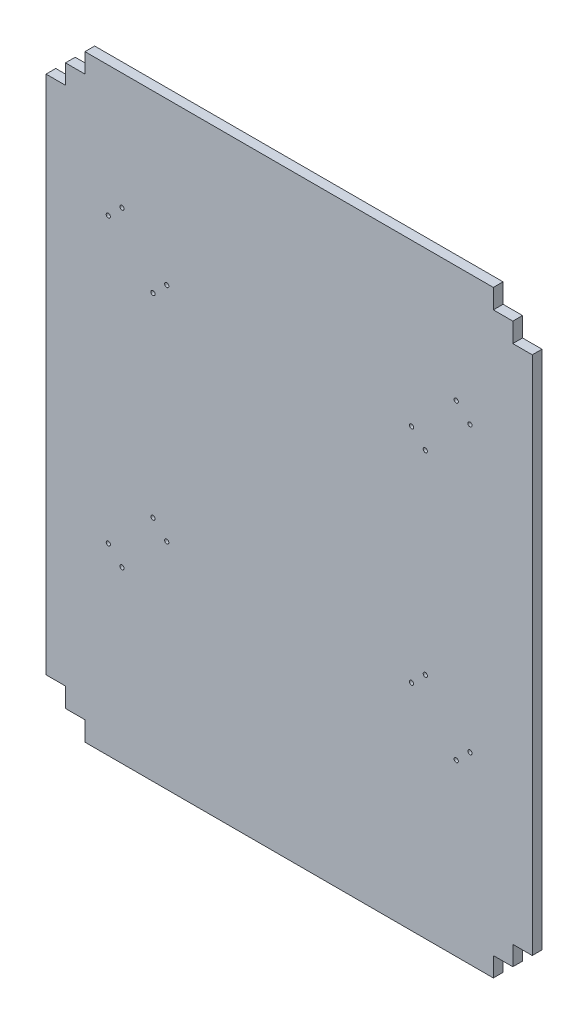
SolidWorks part; units mm, degrees
ref_plane "前视基准面" through (0, 0, 0) normal (0, 0, 1) x (1, 0, 0)
ref_plane "上视基准面" through (0, 0, 0) normal (0, 1, 0) x (1, 0, 0)
ref_plane "右视基准面" through (0, 0, 0) normal (1, 0, 0) x (0, 0, -1)
sketch "草图1" plane through (0, 0, 0) normal (0, 0, 1) x (1, 0, 0)
  line L0 (0, 0) -> (0, -535)
  line L1 (0, -535) -> (20, -535)
  line L2 (20, -535) -> (20, -555)
  line L3 (20, -555) -> (40, -555)
  line L4 (40, -555) -> (40, -575)
  line L5 (40, -575) -> (460, -575)
  line L6 (460, -575) -> (460, -555)
  line L7 (460, -555) -> (480, -555)
  line L8 (480, -555) -> (480, -535)
  line L9 (480, -535) -> (500, -535)
  line L10 (500, -535) -> (500, 0)
  line L11 (0, 0) -> (20, 0)
  line L12 (20, 0) -> (20, 20)
  line L13 (20, 20) -> (40, 20)
  line L14 (40, 20) -> (40, 40)
  line L15 (40, 40) -> (460, 40)
  line L16 (460, 40) -> (460, 20)
  line L17 (460, 20) -> (480, 20)
  line L18 (480, 20) -> (480, 0)
  line L19 (480, 0) -> (500, 0)
  dimension "D1" = 535
  dimension "D2" = 20
  dimension "D3" = 20
  dimension "D4" = 20
  dimension "D5" = 20
  dimension "D6" = 420
  dimension "D7" = 20
  dimension "D8" = 20
  dimension "D9" = 20
  dimension "D10" = 20
  dimension "D11" = 20
  dimension "D12" = 20
  dimension "D13" = 20
  dimension "D14" = 20
  dimension "D15" = 420
extrude "凸台-拉伸1" add sketch "草图1" along normal blind 10
sketch "草图2" plane through (0, 0, 10) normal (0, 0, 1) x (1, 0, 0)
  line L0 (0, 0) -> (0, -140)
  line L1 (0, 0) -> (0, -535) construction
  line L2 (250, 40) -> (250, -620.908)
  line L3 (0, -140) -> (110, -140)
  line L4 (460, 40) -> (40, 40) construction
  line L5 (0, -240) -> (500, -240)
  line L6 (500, -535) -> (500, 0) construction
  line L7 (20, 0) -> (0, 0) construction
  circle A0 centre (64.0381, -94.0381) radius 2.15
  circle A1 centre (78.1802, -79.8959) radius 2.15
  circle A2 centre (110, -140) radius 2.15
  circle A3 centre (124.1421, -125.8579) radius 2.15
  circle A4 centre (390, -140) radius 2.15
  circle A5 centre (375.8579, -125.8579) radius 2.15
  circle A6 centre (435.9619, -94.0381) radius 2.15
  circle A7 centre (421.8198, -79.8959) radius 2.15
  circle A8 centre (421.8198, -400.1041) radius 2.15
  circle A9 centre (435.9619, -385.9619) radius 2.15
  circle A10 centre (375.8579, -354.1421) radius 2.15
  circle A11 centre (390, -340) radius 2.15
  circle A12 centre (124.1421, -354.1421) radius 2.15
  circle A13 centre (110, -340) radius 2.15
  circle A14 centre (78.1802, -400.1041) radius 2.15
  circle A15 centre (64.0381, -385.9619) radius 2.15
  dimension "D1" = 4.3
  dimension "D2" = 4.3
  dimension "D3" = 4.3
  dimension "D4" = 4.3
  dimension "D5" = 140
  dimension "D6" = 110
  dimension "D7" = 240
extrude "切除-拉伸1" cut sketch "草图2" against normal blind 10
